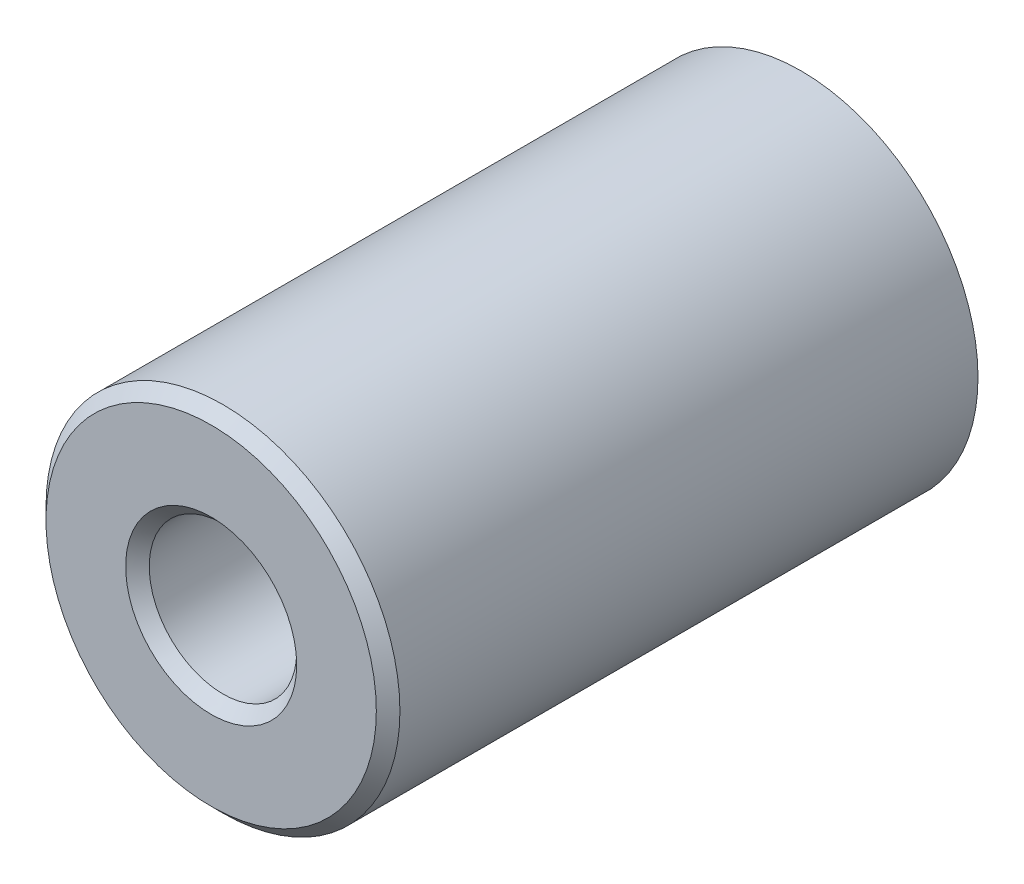
SolidWorks part; units mm, degrees
ref_plane "前视基准面" through (0, 0, 0) normal (0, 0, 1) x (1, 0, 0)
ref_plane "上视基准面" through (0, 0, 0) normal (0, 1, 0) x (1, 0, 0)
ref_plane "右视基准面" through (0, 0, 0) normal (1, 0, 0) x (0, 0, -1)
sketch "草图1" plane through (0, 0, 0) normal (0, 0, 1) x (1, 0, 0)
  circle A0 centre (0, 0) radius 3
  dimension "D1" = 6
extrude "凸台-拉伸1" add sketch "草图1" along normal blind 10
hole_wizard "M3 螺纹孔1" positions "草图2" profile "草图4" tap size "M3" standard "GB" end condition through all
sketch "草图2" plane through (0, 0, 10) normal (0, 0, 1) x (1, 0, 0)
  point P0 (0, 0)
sketch "草图4" plane through (0, 0, 10) normal (1, 0, 0) x (0, -1, 0)
  line L0 (0, 0) -> (0, 10)
  line L1 (0, 10) -> (1.25, 10)
  line L2 (1.25, 10) -> (1.25, 0)
  line L5 (1.25, 0) -> (0, 0)
  line L11 (0, -6.35) -> (0, 107.95) construction
  dimension "通孔螺纹孔钻头直径" = 2.5
  dimension "通孔螺纹孔钻头深度" = 10
cosmetic thread "孔螺蚊线1" parameters "D2"=3
chamfer "倒角1" distance 0.2 angle 45 3 edges at (1.25, 0, 10) (1.25, 0, 0) (3, 0, 10)
